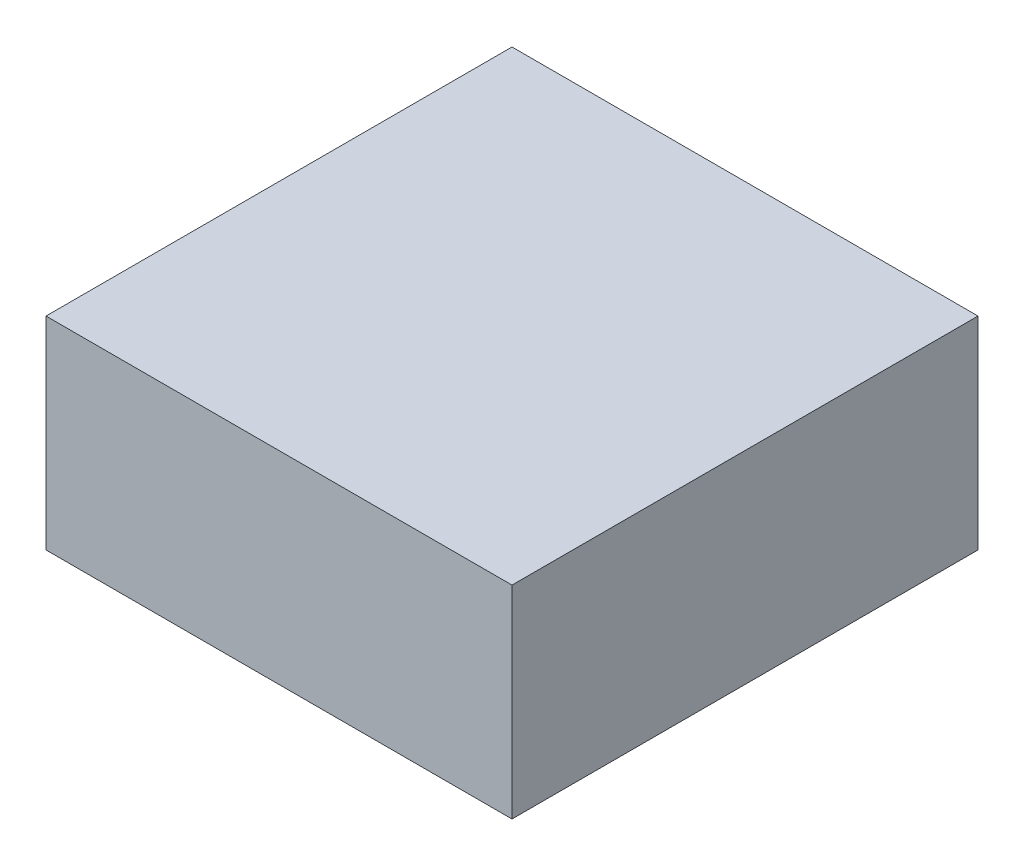
SolidWorks part; units mm, degrees
ref_plane "Front Plane" through (0, 0, 0) normal (0, 0, 1) x (1, 0, 0)
ref_plane "Top Plane" through (0, 0, 0) normal (0, 1, 0) x (1, 0, 0)
ref_plane "Right Plane" through (0, 0, 0) normal (1, 0, 0) x (0, 0, -1)
sketch "Sketch1" plane through (0, 0, 0) normal (0, 1, 0) x (1, 0, 0)
  line L1 (-115, 115) -> (115, 115)
  line L2 (-115, 115) -> (-115, -115)
  line L3 (-115, -115) -> (115, -115)
  line L4 (115, 115) -> (115, -115)
  line L5 (-115, 115) -> (115, -115) construction
  line L6 (-115, -115) -> (115, 115) construction
  point P0 (0, 0)
  dimension "D1" = 230
  dimension "D2" = 230
extrude "Boss-Extrude1" add sketch "Sketch1" along normal blind 100
